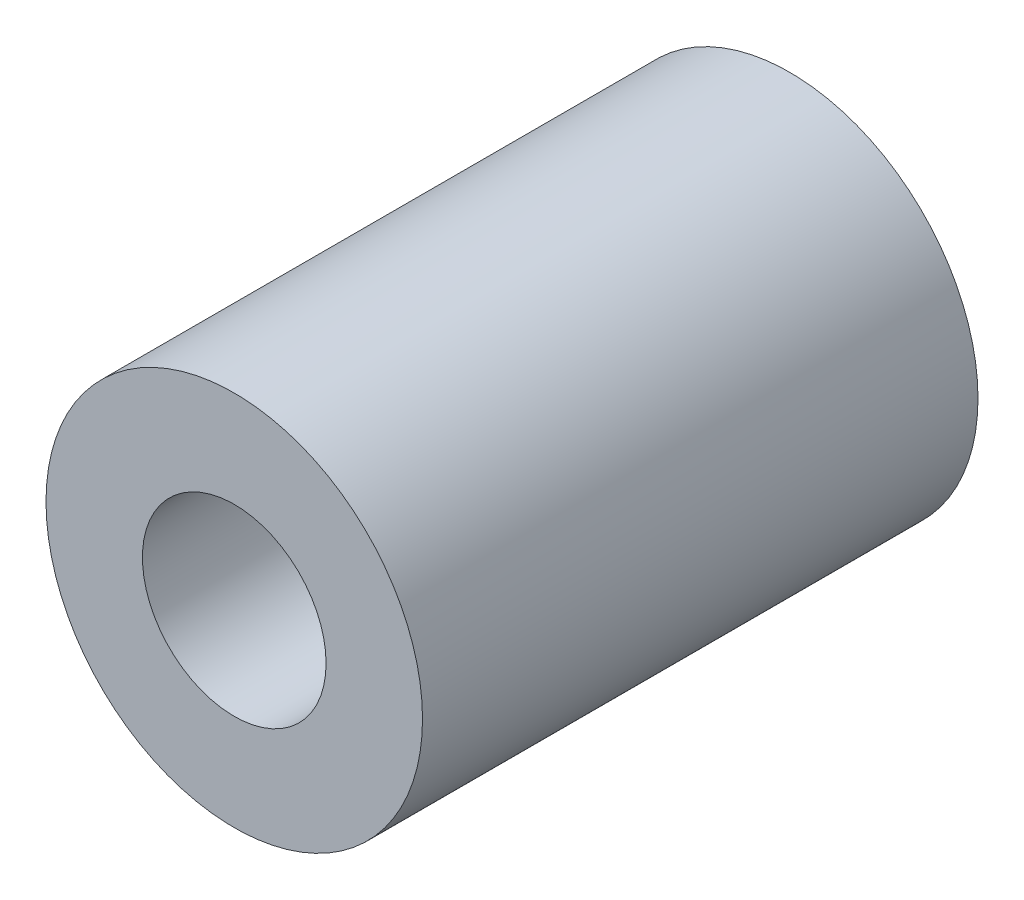
SolidWorks part; units mm, degrees
ref_plane "Front Plane" through (0, 0, 0) normal (0, 0, 1) x (1, 0, 0)
ref_plane "Top Plane" through (0, 0, 0) normal (0, 1, 0) x (1, 0, 0)
ref_plane "Right Plane" through (0, 0, 0) normal (1, 0, 0) x (0, 0, -1)
sketch "Sketch1" plane through (0, 0, 0) normal (0, 0, 1) x (1, 0, 0)
  circle A0 centre (0, 0) radius 14.2875 construction
  circle A2 centre (0, 0) radius 13.0175
  circle A3 centre (0, 0) radius 6.35
  circle A4 centre (0, 0) radius 14.2875 construction
  dimension "D1" = 1.27
  dimension "D2" = 12.7
extrude "Boss-Extrude1" add sketch "Sketch1" along normal up to surface (38.4099 mm away) from surface at 0
